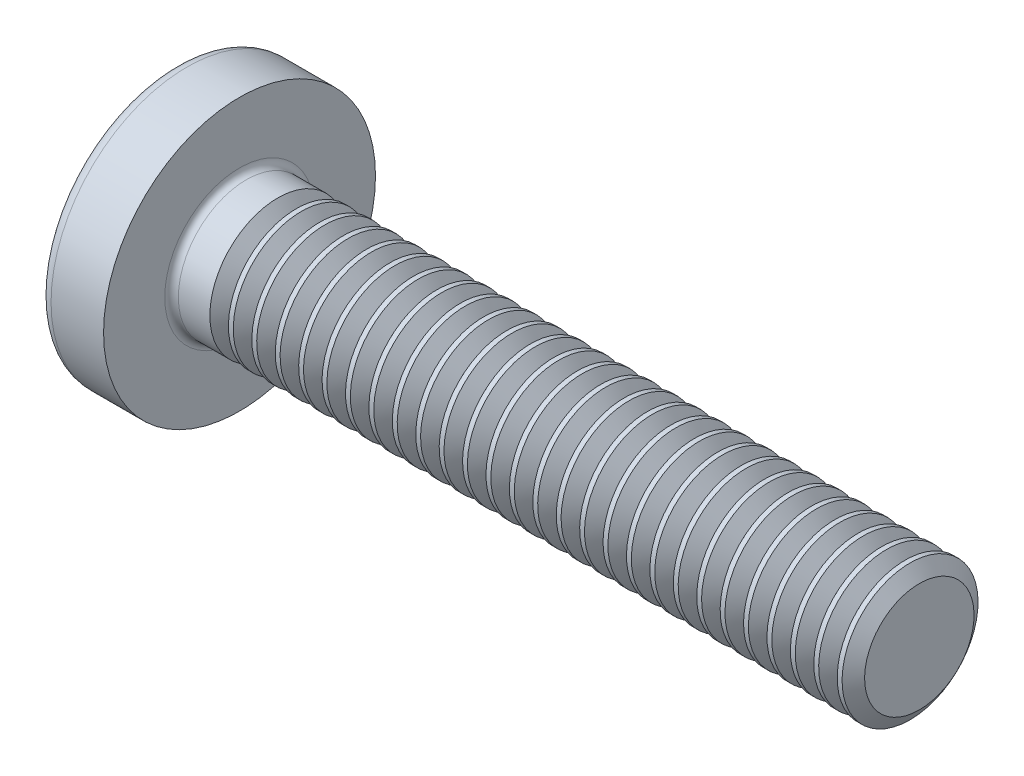
SolidWorks part; units mm, degrees
ref_plane "Plane1" through (0, 0, 0) normal (0, 0, 1) x (1, 0, 0)
ref_plane "Plane2" through (0, 0, 0) normal (0, 1, 0) x (1, 0, 0)
ref_plane "Plane3" through (0, 0, 0) normal (1, 0, 0) x (0, 0, -1)
sketch "BodySke" plane through (0, 0, 0) normal (0, 0, 1) x (1, 0, 0)
  line L0 (3.1, 2) -> (3.1, 4)
  line L1 (3.45, 6.35) -> (3.45, -3.175) construction
  line L2 (-25.4, 0) -> (127, 0) construction
  line L3 (23.1, 0) -> (0, 0)
  line L4 (3.1, 2) -> (23.1, 2)
  line L5 (23.1, 2) -> (23.1, 0)
  line L6 (1.5553, 4) -> (3.1, 4)
  line L8 (3.1, 6.35) -> (3.1, -3.175) construction
  arc A0 (1.2654, 3.8534) -> (0, 0) centre (6.5, 0) ccw
  arc A2 (1.2654, 3.8534) -> (1.5553, 4) centre (1.5553, 3.64) cw
  dimension "Head_crown_rad" = 6.5
  dimension "Head_fillet_rad" = 0.36
  dimension "Length" = 20
  dimension "Head_ht" = 3.1
  dimension "Head_dia" = 8
  dimension "Advance" = 0.7
  dimension "Thread_nom" = 20
  dimension "Diameter" = 4
revolve "Base-Revolve" add sketch "BodySke"
cosmetic thread "ThreadCosmetic" [suppressed]
fillet "Fillet1" radius 0.2 1 edges at (3.1, 0, 2)
sketch "Sketch3" plane through (0, 0, 0) normal (1, 0, 0) x (0, 0, -1)
  line L0 (0.515, -2.15) -> (-0.515, -2.15)
  line L1 (0.515, -2.15) -> (0.515, 2.15)
  line L2 (-0.515, 2.15) -> (0.515, 2.15)
  line L3 (-0.515, 2.15) -> (-0.515, -2.15)
  dimension "Cross_dia" = 4.3
  dimension "D1" = 2.15
  dimension "Cross_width" = 1.03
  dimension "D2" = 0.515
ref_plane "Plane4" through (2.34, 0, 0) normal (1, 0, 0) x (0, 0, -1)
sketch "Sketch4" plane through (2.34, 0, 0) normal (1, 0, 0) x (0, 0, -1)
  line L0 (0.515, -0.9833) -> (-0.515, -0.9833)
  line L1 (0.515, -0.9833) -> (0.515, 0.9833)
  line L2 (-0.515, 0.9833) -> (0.515, 0.9833)
  line L3 (-0.515, 0.9833) -> (-0.515, -0.9833)
  dimension "D1" = 1.03
  dimension "D2" = 1.9666
  dimension "D3" = 0.515
  dimension "D4" = 0.9833
loft "Recess" cut profiles "Sketch3", "Sketch4"
pattern_circular "RecPat" count 2 every 90 about axis through (0, 0, 0) along (1, 0, 0) of "Recess"
sketch "RecCorSke" plane through (0, 0, 0) normal (0, 0, 1) x (1, 0, 0)
  line L0 (-3.175, 0) -> (15.875, 0) construction
  line L1 (-25.4, 0) -> (127, 0) construction
  line L2 (0, 0) -> (0, 1.0146)
  line L3 (0, 1.0146) -> (2.34, 0.851)
  line L4 (2.34, 0.851) -> (2.6165, 0)
  line L5 (2.6165, 0) -> (0, 0)
  dimension "Diameter" = 1.702
  dimension "Depth" = 2.34
  dimension "Draft_angle" = 4
  dimension "Bottom_angle" = 18
revolve "RecessCore" cut sketch "RecCorSke" angle 360 about L0
sketch "ThdSchSke" plane through (0, 0, 0) normal (0, 0, 1) x (1, 0, 0)
  line L0 (4.5, -1.61) -> (4.2269, -2)
  line L1 (4.5, -1.61) -> (4.7731, -2)
  line L2 (4.7731, -2) -> (4.7731, -2.5)
  line L3 (-3.175, 0) -> (5.1513, 0) construction
  line L5 (4.7731, -2.5) -> (4.2269, -2.5)
  line L6 (4.2269, -2.5) -> (4.2269, -2)
  dimension "Diameter" = 4
  dimension "SideAngle" = 55
  dimension "VeeAngle" = 70
  dimension "Thread_minor" = 3.22
  dimension "Overcut" = 5
  dimension "Start" = 4.5
revolve "ThreadSchematic" cut sketch "ThdSchSke" angle 360 about L3
pattern_linear "ThdSchPat" count 28 spacing 0.6889 along (1, 0, 0) of "ThreadSchematic"
equation "\"D1@Sketch3\" = \"Cross_dia@Sketch3\" / 2"
equation "\"D2@Sketch3\" = \"Cross_width@Sketch3\" / 2"
equation "\"Depth@RecCorSke\" = \"Cross_depth@Plane4\""
equation "\"D1@Sketch4\" = \"Cross_width@Sketch3\""
equation "\"D2@Sketch4\" = \"Cross_dia@Sketch3\" - 2.0 * \"Cross_depth@Plane4\" * tan(26.5  * 0.017453292)"
equation "\"D3@Sketch4\" = \"D1@Sketch4\" / 2"
equation "\"D4@Sketch4\" = \"D2@Sketch4\" / 2"
equation "\"Thread_length@ThreadCosmetic\" = ((sgn( (\"Length@BodySke\" - \"Advance@BodySke\" * 2.0 ) - \"Thread_nom@BodySke\" )-1)*( (\"Length@BodySke\" - \"Advance@BodySke\" * 2.0 ) - \"Thread_nom@BodySke\" ))/-2+ \"Thread_nom@BodySke\""
equation "\"Thread_minor@ThdSchSke\" = \"Thread_minor@ThreadCosmetic\""
equation "\"Diameter@ThdSchSke\" = \"Diameter@BodySke\""
equation "\"Overcut@ThdSchSke\" = \"Diameter@BodySke\" * 1.25"
equation "\"Start@ThdSchSke\" = \"Head_ht@BodySke\" + \"Length@BodySke\" - \"Thread_length@ThreadCosmetic\"  '---Non-countersunk---"
equation "\"Num_threads@ThdSchPat\" = int( \"Thread_length@ThreadCosmetic\" / \"Advance@BodySke\" + 0.999 )  + 1"
equation "\"Advance@ThdSchPat\" = \"Thread_length@ThreadCosmetic\" /  (\"Num_threads@ThdSchPat\" - 1) 'relax it"
